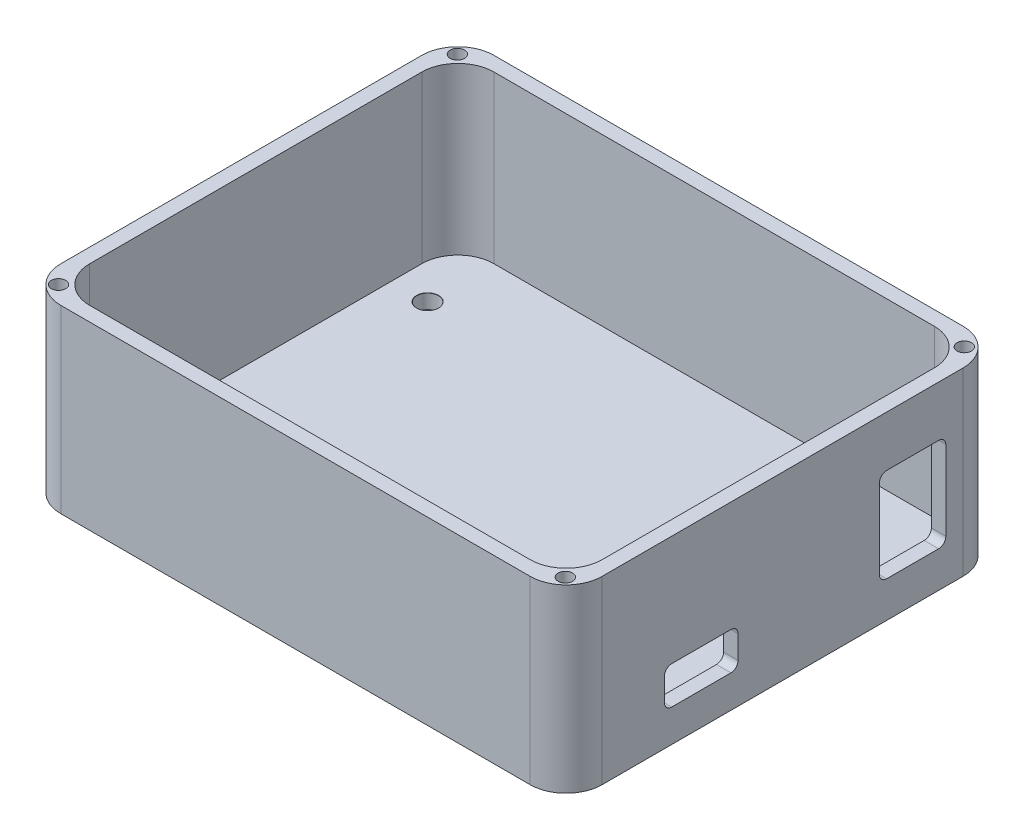
SolidWorks part; units mm, degrees
ref_plane "Ebene vorne" through (0, 0, 0) normal (0, 0, 1) x (1, 0, 0)
ref_plane "Ebene oben" through (0, 0, 0) normal (0, 1, 0) x (1, 0, 0)
ref_plane "Ebene rechts" through (0, 0, 0) normal (1, 0, 0) x (0, 0, -1)
sketch "Skizze1" plane through (0, 0, 0) normal (0, 1, 0) x (1, 0, 0)
  line L1 (-37.5, -30) -> (37.5, -30)
  line L2 (-37.5, -30) -> (-37.5, 30)
  line L3 (-37.5, 30) -> (37.5, 30)
  line L4 (37.5, -30) -> (37.5, 30)
  line L5 (-37.5, -30) -> (37.5, 30) construction
  line L6 (-37.5, 30) -> (37.5, -30) construction
  point P0 (0, 0)
  dimension "D1" = 75
  dimension "D2" = 60
extrude "Aufsatz-Linear austragen1" add sketch "Skizze1" along normal blind 25
shell "Wandung1" thickness 2
fillet "Verrundung1" radius 5 8 edges at (35.5, 13.5, 28) (-35.5, 13.5, 28) (35.5, 13.5, -28) (-35.5, 13.5, -28) (37.5, 12.5, -30) (-37.5, 12.5, -30) (-37.5, 12.5, 30) (37.5, 12.5, 30)
sketch "Skizze2" plane through (37.5, 0, 0) normal (1, 0, 0) x (0, 0, -1)
  line L0 (30, 25) -> (30, 0) construction
  line L1 (13.4, 5) -> (22.6, 5)
  line L2 (13.4, 5) -> (13.4, 18)
  line L3 (13.4, 18) -> (22.6, 18)
  line L4 (22.6, 5) -> (22.6, 18)
  line L5 (-25, 0) -> (25, 0) construction
  dimension "D1" = 7.4
  dimension "D2" = 9.2
  dimension "D3" = 5
  dimension "D4" = 13
extrude "Schnitt-Linear austragen1" cut sketch "Skizze2" against normal blind 25
fillet "Verrundung2" radius 1 4 edges at (36.5, 5, -13.4) (36.5, 5, -22.6) (36.5, 18, -22.6) (36.5, 18, -13.4)
sketch "Skizze3" plane through (37.5, 0, 0) normal (1, 0, 0) x (0, 0, -1)
  line L0 (-30, 0) -> (-30, 25) construction
  line L1 (-16.38, 9.7) -> (-6.18, 9.7)
  line L2 (-16.38, 9.7) -> (-16.38, 4.5)
  line L3 (-16.38, 4.5) -> (-6.18, 4.5)
  line L4 (-6.18, 9.7) -> (-6.18, 4.5)
  line L5 (-25, 0) -> (25, 0) construction
  dimension "D1" = 13.62
  dimension "D2" = 4.5
  dimension "D3" = 5.2
  dimension "D4" = 10.2
extrude "Schnitt-Linear austragen2" cut sketch "Skizze3" against normal blind 25
fillet "Verrundung3" radius 1 4 edges at (36.5, 9.7, 16.38) (36.5, 9.7, 6.18) (36.5, 4.5, 6.18) (36.5, 4.5, 16.38)
hole_wizard "Ø3.0 (3) Durchmesser Bohrung1" positions "Skizze4" profile "Skizze5" hole size "Ø3.0" standard "DIN" end condition through all
sketch "Skizze4" plane through (0, 2, 0) normal (0, 1, 0) x (1, 0, 0)
  point P0 (21.5461, 23.9742)
  point P2 (-30.533, 18.8389)
  point P4 (-30.533, -9.0706)
  point P6 (20.2623, -24.3091)
sketch "Skizze5" plane through (21.5461, 2, -23.9742) normal (1, 0, 0) x (0, 0, 1)
  line L0 (0, 0) -> (0, 2)
  line L1 (0, 2) -> (1.5, 2)
  line L2 (1.5, 2) -> (1.5, 0.025)
  line L3 (1.5, 0.025) -> (1.525, 0)
  line L4 (1.525, 0) -> (0, 0)
  line L5 (-1.5, 0.025) -> (-1.525, 0) construction
  line L6 (0, -6.35) -> (0, 107.95) construction
  dimension "Bohrerdurchmesser" = 3
  dimension "Bohrungstiefe" = 2
  dimension "Senkdurchmesser2 (Oben)" = 3.05
  dimension "Senkwinkel2 (Oben)" = 90
hole_wizard "Ø2.0 (2) Durchmesser Bohrung1" positions "Skizze6" profile "Skizze7" hole size "Ø2.0" standard "DIN"
sketch "Skizze6" plane through (0, 28, 0) normal (0, 1, 0) x (1, 0, 0)
  point P0 (-35.1659, 27.6025)
  point P2 (35.0543, 27.6025)
  point P4 (35.0543, -27.6583)
  point P6 (-35.1659, -27.6583)
sketch "Skizze7" plane through (-35.1659, 28, -27.6025) normal (1, 0, 0) x (0, 0, 1)
  line L0 (0, 0) -> (0, 20.6009)
  line L1 (0, 20.6009) -> (1, 20)
  line L2 (1, 20) -> (1, 0.025)
  line L3 (1, 0.025) -> (1.025, 0)
  line L4 (1.025, 0) -> (0, 0)
  line L5 (-1, 0.025) -> (-1.025, 0) construction
  line L6 (0, 20.6009) -> (-1, 20) construction
  line L7 (0, -6.35) -> (0, 107.95) construction
  dimension "Bohrerdurchmesser" = 2
  dimension "Bohrungstiefe" = 20
  dimension "Senkdurchmesser2 (Oben)" = 2.05
  dimension "Senkwinkel2 (Oben)" = 90
  dimension "Spitzenwinkel" = 118
